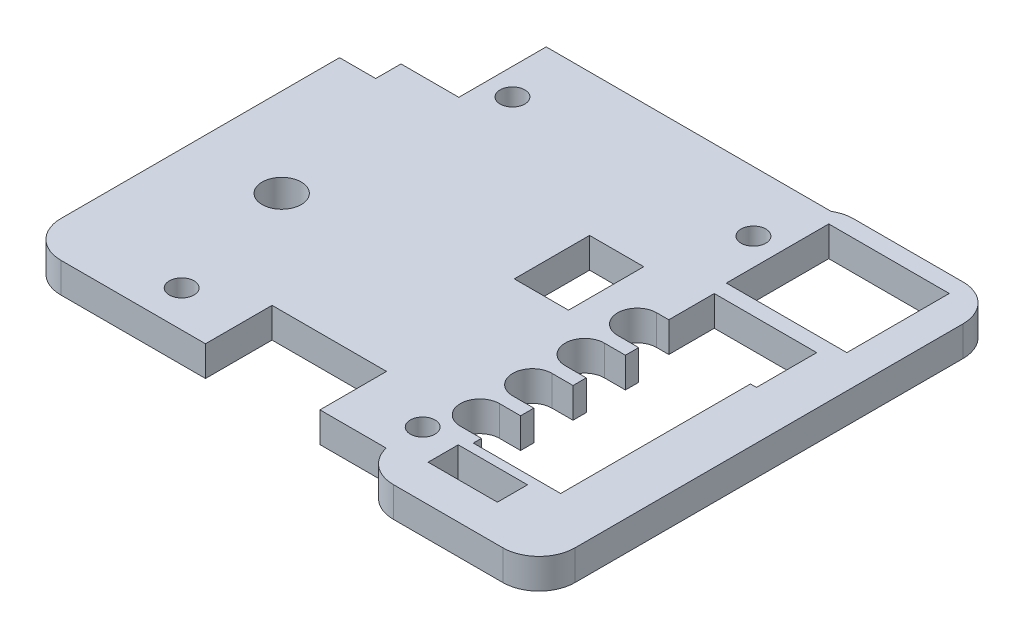
SolidWorks part; units mm, degrees
ref_plane "前视基准面" through (0, 0, 0) normal (0, 0, 1) x (1, 0, 0)
ref_plane "上视基准面" through (0, 0, 0) normal (0, 1, 0) x (1, 0, 0)
ref_plane "右视基准面" through (0, 0, 0) normal (1, 0, 0) x (0, 0, -1)
sketch "草图1" plane through (0, 0, 0) normal (0, 1, 0) x (1, 0, 0)
  line L0 (6, 0.3) -> (143.8, 0.3)
  line L1 (6, 0) -> (143.8, 0) construction
  line L2 (0, -6) -> (0, -68.8) construction
  line L3 (6, -74.8) -> (143.8, -74.8) construction
  line L4 (149.8, -6) -> (149.8, -68.8) construction
  line L5 (150.1, -6) -> (150.1, -68.8)
  line L6 (6, -75.1) -> (143.8, -75.1)
  line L7 (-0.3, -6) -> (-0.3, -68.8)
  arc A0 (143.8, 0) -> (149.8, -6) centre (143.8, -6) cw construction
  arc A1 (143.8, -74.8) -> (149.8, -68.8) centre (143.8, -68.8) ccw construction
  arc A2 (0, -68.8) -> (6, -74.8) centre (6, -68.8) ccw construction
  arc A3 (6, 0) -> (0, -6) centre (6, -6) ccw construction
  arc A4 (143.8, 0.3) -> (150.1, -6) centre (143.8, -6) cw
  arc A5 (143.8, -75.1) -> (150.1, -68.8) centre (143.8, -68.8) ccw
  arc A6 (-0.3, -68.8) -> (6, -75.1) centre (6, -68.8) ccw
  arc A7 (6, 0.3) -> (-0.3, -6) centre (6, -6) ccw
  point P7 (149.8, 0)
  point P12 (0, -74.8)
  point P15 (0, 0)
  dimension "D3" = 6
  dimension "D1" = 74.8
  dimension "D2" = 149.8
  dimension "D4" = 0.3
sketch "草图2" plane through (0, 0, 0) normal (0, -1, 0) x (-1, 0, 0)
  line L0 (-122.6, -55.35) -> (-108.9, -55.35) construction
  line L1 (-122.6, -69.85) -> (-108.9, -69.85) construction
  line L2 (-122.6, -69.85) -> (-122.6, -63.95) construction
  line L3 (-122.6, -63.95) -> (-108.9, -63.95) construction
  line L4 (-108.9, -69.85) -> (-108.9, -63.95) construction
  line L5 (-135.3, -1.25) -> (-35.3, -1.25) construction
  line L6 (-135.3, -1.25) -> (-135.3, -73.55) construction
  line L7 (-135.3, -73.55) -> (-35.3, -73.55) construction
  line L8 (-35.3, -1.25) -> (-35.3, -73.55) construction
  line L9 (-108.9, -61.25) -> (-108.9, -55.35) construction
  line L10 (-122.6, -61.25) -> (-108.9, -61.25) construction
  line L11 (-122.6, -61.25) -> (-122.6, -55.35) construction
  line L12 (-122.6, -46.75) -> (-108.9, -46.75) construction
  line L13 (-108.9, -52.65) -> (-108.9, -46.75) construction
  line L14 (-122.6, -52.65) -> (-108.9, -52.65) construction
  line L15 (-122.6, -52.65) -> (-122.6, -46.75) construction
  line L16 (-122.6, -38.15) -> (-108.9, -38.15) construction
  line L17 (-108.9, -44.05) -> (-108.9, -38.15) construction
  line L18 (-122.6, -44.05) -> (-108.9, -44.05) construction
  line L19 (-122.6, -44.05) -> (-122.6, -38.15) construction
  line L20 (0, -6) -> (0, -68.8) construction
  line L21 (-35.3, -73.55) -> (-0.8, -73.55) construction
  line L22 (-120.25, -26.65) -> (-111.25, -26.65) construction
  line L23 (-120.25, -26.65) -> (-120.25, -33.15) construction
  line L24 (-120.25, -33.15) -> (-111.25, -33.15) construction
  line L25 (-111.25, -26.65) -> (-111.25, -33.15) construction
  line L26 (-85.8, -48.75) -> (-81.1, -48.75) construction
  line L27 (-85.8, -48.75) -> (-85.8, -58.15) construction
  line L28 (-85.8, -58.15) -> (-81.1, -58.15) construction
  line L29 (-81.1, -48.75) -> (-81.1, -58.15) construction
  line L30 (-71.5, -48.65) -> (-68.2, -48.65) construction
  line L31 (-71.5, -48.65) -> (-71.5, -57.55) construction
  line L32 (-71.5, -57.55) -> (-68.2, -57.55) construction
  line L33 (-68.2, -48.65) -> (-68.2, -57.55) construction
  line L34 (-43.1, -45.05) -> (-38.6, -45.05) construction
  line L35 (-43.1, -45.05) -> (-43.1, -59.05) construction
  line L36 (-43.1, -59.05) -> (-38.6, -59.05) construction
  line L37 (-38.6, -45.05) -> (-38.6, -59.05) construction
  line L38 (-45.3, -61.55) -> (-40.8, -61.55) construction
  line L39 (-45.3, -61.55) -> (-45.3, -66.05) construction
  line L40 (-45.3, -66.05) -> (-40.8, -66.05) construction
  line L41 (-40.8, -61.55) -> (-40.8, -66.05) construction
  line L42 (-0.8, -73.55) -> (-0.8, -1.25) construction
  line L43 (-0.8, -1.25) -> (-35.3, -1.25) construction
  line L44 (-149.8, -6) -> (-149.8, -68.8) construction
  line L45 (-30.8, -34.65) -> (-27.3, -34.65) construction
  line L46 (-30.8, -34.65) -> (-30.8, -40.15) construction
  line L47 (-30.8, -40.15) -> (-27.3, -40.15) construction
  line L48 (-27.3, -34.65) -> (-27.3, -40.15) construction
  line L49 (-120.75, -33.65) -> (-110.75, -33.65)
  line L50 (-110.75, -26.15) -> (-110.75, -33.65)
  line L51 (-120.75, -26.15) -> (-110.75, -26.15)
  line L52 (-120.75, -26.15) -> (-120.75, -33.65)
  line L53 (-86.3, -48.25) -> (-86.3, -58.65)
  line L54 (-86.3, -58.65) -> (-80.6, -58.65)
  line L55 (-80.6, -48.25) -> (-80.6, -58.65)
  line L56 (-86.3, -48.25) -> (-80.6, -48.25)
  line L57 (-72, -48.15) -> (-72, -58.05)
  line L58 (-72, -58.05) -> (-67.7, -58.05)
  line L59 (-67.7, -48.15) -> (-67.7, -58.05)
  line L60 (-72, -48.15) -> (-67.7, -48.15)
  line L61 (-31.3, -34.15) -> (-31.3, -40.65)
  line L62 (-31.3, -40.65) -> (-26.8, -40.65)
  line L63 (-26.8, -34.15) -> (-26.8, -40.65)
  line L64 (-31.3, -34.15) -> (-26.8, -34.15)
  line L65 (-43.6, -44.55) -> (-43.6, -59.55)
  line L66 (-43.6, -59.55) -> (-38.1, -59.55)
  line L67 (-38.1, -44.55) -> (-38.1, -59.55)
  line L68 (-43.6, -44.55) -> (-38.1, -44.55)
  line L69 (-45.8, -61.05) -> (-45.8, -66.55)
  line L70 (-45.8, -66.55) -> (-40.3, -66.55)
  line L71 (-40.3, -61.05) -> (-40.3, -66.55)
  line L72 (-45.8, -61.05) -> (-40.3, -61.05)
  line L73 (-122.9, -44.35) -> (-108.6, -44.35)
  line L74 (-108.6, -44.35) -> (-108.6, -37.85)
  line L75 (-122.9, -37.85) -> (-108.6, -37.85)
  line L76 (-122.9, -44.35) -> (-122.9, -37.85)
  line L77 (-122.9, -52.95) -> (-108.6, -52.95)
  line L78 (-108.6, -52.95) -> (-108.6, -46.45)
  line L79 (-122.9, -46.45) -> (-108.6, -46.45)
  line L80 (-122.9, -52.95) -> (-122.9, -46.45)
  line L81 (-122.9, -61.55) -> (-108.6, -61.55)
  line L82 (-108.6, -61.55) -> (-108.6, -55.05)
  line L83 (-122.9, -55.05) -> (-108.6, -55.05)
  line L84 (-122.9, -61.55) -> (-122.9, -55.05)
  line L85 (-122.9, -70.15) -> (-108.6, -70.15)
  line L86 (-108.6, -70.15) -> (-108.6, -63.65)
  line L87 (-122.9, -63.65) -> (-108.6, -63.65)
  line L88 (-122.9, -70.15) -> (-122.9, -63.65)
  circle A0 centre (-103.2, -9.35) radius 1.65 construction
  circle A1 centre (-103.2, -64.25) radius 1.65 construction
  circle A2 centre (-63.2, -64.25) radius 1.65 construction
  circle A3 centre (-63.2, -9.35) radius 1.65 construction
  circle A4 centre (-130.8, -5.6) radius 1.25 construction
  circle A5 centre (-131.1, -55.65) radius 1.25 construction
  circle A6 centre (-47.7, -4.85) radius 1.25 construction
  circle A7 centre (-48.1, -68.75) radius 1.25 construction
  circle A8 centre (-22.8, -70.3) radius 1.25 construction
  circle A9 centre (-5.05, -71.05) radius 1.25 construction
  circle A10 centre (-5.05, -3.25) radius 1.25 construction
  circle A11 centre (-19, -37.4) radius 3.6 construction
  circle A12 centre (-103.2, -9.35) radius 2.05
  circle A13 centre (-63.2, -9.35) radius 2.05
  circle A14 centre (-63.2, -64.25) radius 2.05
  circle A15 centre (-103.2, -64.25) radius 2.05
  circle A16 centre (-19, -37.4) radius 4.1
  circle A17 centre (-130.8, -5.6) radius 1.75
  circle A18 centre (-131.1, -55.65) radius 1.75
  circle A19 centre (-48.1, -68.75) radius 1.75
  circle A20 centre (-22.8, -70.3) radius 1.75
  circle A21 centre (-5.05, -71.05) radius 1.75
  circle A22 centre (-5.05, -3.25) radius 1.75
  circle A23 centre (-47.7, -4.85) radius 1.75
  point P22 (0, -37.4)
  point P23 (-135.3, -37.4)
  point P28 (-115.75, -33.15)
  point P29 (-115.75, -38.15)
  point P30 (-111.25, -29.9)
  point P31 (-108.9, -41.1)
  point P79 (-0.8, -37.4)
  point P81 (-27.3, -37.4)
  dimension "D21" = 3.3
  dimension "D34" = 2.5
  dimension "D53" = 7.2
  dimension "D1" = 13.7
  dimension "D2" = 5.9
  dimension "D3" = 72.3
  dimension "D4" = 3.7
  dimension "D5" = 12.7
  dimension "D7" = 14.5
  dimension "D8" = 100
  dimension "D9" = 2.7
  dimension "D10" = 9
  dimension "D11" = 6.5
  dimension "D12" = 11.2
  dimension "D13" = 15.4
  dimension "D14" = 9.4
  dimension "D15" = 4.7
  dimension "D16" = 23.1
  dimension "D17" = 3.3
  dimension "D18" = 8.9
  dimension "D19" = 16
  dimension "D20" = 37.4
  dimension "D22" = 8.1
  dimension "D23" = 32.1
  dimension "D24" = 40
  dimension "D25" = 9.3
  dimension "D26" = 14
  dimension "D27" = 4.5
  dimension "D28" = 4.5
  dimension "D29" = 4.5
  dimension "D30" = 3.3
  dimension "D31" = 5.5
  dimension "D32" = 7.5
  dimension "D33" = 14.5
  dimension "D35" = 34.5
  dimension "D36" = 2
  dimension "D37" = 4.25
  dimension "D38" = 2.5
  dimension "D39" = 3.25
  dimension "D40" = 22
  dimension "D41" = 4.8
  dimension "D42" = 12.8
  dimension "D43" = 3.6
  dimension "D44" = 12.4
  dimension "D45" = 4.35
  dimension "D46" = 4.5
  dimension "D47" = 4.2
  dimension "D48" = 17.9
  dimension "D49" = 18.2
  dimension "D50" = 3.5
  dimension "D51" = 5.5
  dimension "D52" = 8.3
  dimension "D54" = 0.4
  dimension "D55" = 0.5
  dimension "D56" = 0.5
  dimension "D57" = 0.5
  dimension "D58" = 0.3
  dimension "D6" = 4
sketch "草图3" plane through (0, 0, 0) normal (0, 1, 0) x (1, 0, 0)
  line L0 (135.3, -1.25) -> (135.3, -73.55) construction
  line L1 (143.8, 0) -> (135.3, 0)
  line L2 (149.8, -6) -> (149.8, -68.8)
  line L3 (143.8, -74.8) -> (135.3, -74.8)
  line L4 (135.3, 0) -> (135.3, -74.8)
  line L5 (6, -74.8) -> (143.8, -74.8) construction
  arc A0 (143.8, 0) -> (149.8, -6) centre (143.8, -6) cw
  arc A1 (149.8, -68.8) -> (143.8, -74.8) centre (143.8, -68.8) cw
  point P17 (149.8, 0)
  dimension "D1" = 6
sketch "草图4" plane through (0, 0, 0) normal (0, 1, 0) x (1, 0, 0)
  line L0 (122.9, -62.85) -> (108.6, -62.85)
  line L1 (122.6, -63.15) -> (108.9, -63.15) construction
  line L2 (122.6, -63.15) -> (122.6, -70.65) construction
  line L3 (122.6, -70.65) -> (108.9, -70.65) construction
  line L4 (108.9, -63.15) -> (108.9, -70.65) construction
  line L5 (122.6, -69.85) -> (122.6, -63.95) construction
  line L6 (108.6, -62.85) -> (108.6, -70.95)
  line L7 (108.9, -69.85) -> (108.9, -63.95) construction
  line L8 (122.6, -54.55) -> (108.9, -54.55) construction
  line L9 (108.9, -54.55) -> (108.9, -62.05) construction
  line L10 (122.6, -62.05) -> (108.9, -62.05) construction
  line L11 (122.6, -54.55) -> (122.6, -62.05) construction
  line L12 (122.6, -45.95) -> (108.9, -45.95) construction
  line L13 (108.9, -45.95) -> (108.9, -53.45) construction
  line L14 (122.6, -53.45) -> (108.9, -53.45) construction
  line L15 (122.6, -45.95) -> (122.6, -53.45) construction
  line L16 (122.6, -37.35) -> (108.9, -37.35) construction
  line L17 (108.9, -37.35) -> (108.9, -44.85) construction
  line L18 (122.6, -44.85) -> (108.9, -44.85) construction
  line L19 (122.6, -37.35) -> (122.6, -44.85) construction
  line L20 (122.9, -70.95) -> (108.6, -70.95)
  line L21 (122.9, -62.85) -> (122.9, -70.95)
  line L22 (122.9, -54.25) -> (108.6, -54.25)
  line L23 (108.6, -54.25) -> (108.6, -62.35)
  line L24 (122.9, -62.35) -> (108.6, -62.35)
  line L25 (122.9, -54.25) -> (122.9, -62.35)
  line L26 (122.9, -45.65) -> (108.6, -45.65)
  line L27 (108.6, -45.65) -> (108.6, -53.75)
  line L28 (122.9, -53.75) -> (108.6, -53.75)
  line L29 (122.9, -45.65) -> (122.9, -53.75)
  line L30 (122.9, -37.05) -> (108.6, -37.05)
  line L31 (108.6, -37.05) -> (108.6, -45.15)
  line L32 (122.9, -45.15) -> (108.6, -45.15)
  line L33 (122.9, -37.05) -> (122.9, -45.15)
  point P11 (108.9, -66.9)
  point P12 (108.9, -66.9)
  dimension "D1" = 7.5
  dimension "D3" = 1.1
  dimension "D4" = 0.3
  dimension "D2" = 4
extrude "拉伸-薄壁1" add sketch "草图2" along normal blind 5 thin contours A13 | A12 | A14 | A15
sketch "草图6" plane through (0, 0, 0) normal (0, 1, 0) x (1, 0, 0)
  line L0 (127.2, 1.45) -> (109.0462, 1.45)
  line L1 (133.2, -4.55) -> (133.2, -68.95)
  line L2 (127.2, -74.95) -> (109.0462, -74.95)
  line L3 (33.4345, -36.75) -> (43.3021, -36.75) construction
  line L4 (63.2, 0.65) -> (106.0528, 0.65)
  line L6 (63.2, 0.65) -> (45.7, 0.65)
  line L10 (122.9, -70.95) -> (108.6, -70.95) construction
  line L11 (108.6, -62.85) -> (108.6, -70.95) construction
  line L12 (43.2, -1.85) -> (43.2, -64.3)
  line L13 (103.2, -70.3) -> (49.2, -70.3)
  circle A1 centre (103.2, -64.25) radius 6.05 construction
  arc A3 (133.2, -4.55) -> (127.2, 1.45) centre (127.2, -4.55) ccw
  arc A4 (109.0462, -74.95) -> (103.2, -70.3) centre (109.0462, -68.95) cw
  circle A5 centre (63.2, -64.25) radius 6.05 construction
  arc A6 (133.2, -68.95) -> (127.2, -74.95) centre (127.2, -68.95) cw
  arc A7 (109.0462, 1.45) -> (106.0528, 0.65) centre (109.0462, -4.55) ccw
  arc A9 (43.2, -64.3) -> (49.2, -70.3) centre (49.2, -64.3) ccw
  circle A10 centre (103.2, -9.35) radius 2.05 construction
  circle A11 centre (103.2, -64.25) radius 2.05 construction
  circle A12 centre (63.2, -64.25) radius 2.05 construction
  circle A13 centre (103.2, -9.35) radius 2.05
  circle A14 centre (103.2, -64.25) radius 2.05
  circle A15 centre (63.2, -64.25) radius 2.05
  circle A16 centre (63.2, -9.35) radius 2.05 construction
  circle A17 centre (63.2, -9.35) radius 2.05
  arc A18 (45.7, 0.65) -> (43.2, -1.85) centre (45.7, -1.85) ccw
  point P37 (105.6, -74.95)
  point P42 (130.9, -6.15)
  dimension "D6" = 6
  dimension "D7" = 5
  dimension "D8" = 6
  dimension "D9" = 6
  dimension "D10" = 6
  dimension "D11" = 6
  dimension "D2" = 27.5
  dimension "D3" = 4
  dimension "D4" = 3
  dimension "D5" = 20
  dimension "D12" = 30
  dimension "D13" = 10
extrude "凸台-拉伸1" add sketch "草图6" against normal up to surface (5 mm away) up to face at (97.15, -5, 9.35)
sketch "草图7" plane through (0, -5, 3) normal (0, -1, 0) x (1, 0, 0)
  line L9 (80.466, 15.85) -> (96.6871, 15.85) construction
  line L43 (107.2, -14.628) -> (107.2, -27.7853) construction
  line L44 (108.9, 22) -> (108.9, 67) construction
  line L45 (122.6, 67) -> (108.9, 67) construction
  line L46 (122.6, 22) -> (122.6, 67) construction
  line L47 (122.6, 22) -> (108.9, 22) construction
  line L48 (120.2, 9.55) -> (113.2, 9.55)
  line L49 (120.2, 4.55) -> (120.2, 9.55)
  line L50 (113.2, 4.55) -> (120.2, 4.55)
  line L51 (113.2, 9.55) -> (113.2, 4.55)
  line L52 (80.4, 48.65) -> (80.4, 33.65)
  line L53 (85.4, 48.65) -> (80.4, 48.65)
  line L54 (97.9, 36.55) -> (89.9, 36.55)
  line L55 (97.9, 25.55) -> (97.9, 36.55)
  line L56 (89.9, 25.55) -> (97.9, 25.55)
  line L57 (89.9, 36.55) -> (89.9, 25.55)
  line L58 (66.4, 33.65) -> (80.4, 33.65)
  line L59 (50.4, 54.65) -> (50.4, 33.65)
  line L60 (85.4, 54.65) -> (50.4, 54.65)
  line L61 (85.4, 48.65) -> (85.4, 54.65)
  line L62 (47.4, 10.15) -> (66.4, 10.15)
  line L63 (47.4, 33.65) -> (47.4, 10.15)
  line L64 (50.4, 33.65) -> (47.4, 33.65)
  line L65 (66.4, 10.15) -> (66.4, 15.35)
  line L66 (66.4, 24.35) -> (72.4, 24.35)
  line L67 (66.4, 24.35) -> (66.4, 33.65)
  line L68 (72.4, 15.35) -> (66.4, 15.35)
  line L69 (122.9, 21.7) -> (122.9, 67.3)
  line L70 (122.9, 67.3) -> (108.6, 67.3)
  line L71 (72.4, 24.35) -> (72.4, 15.35)
  line L72 (92.2, 15.35) -> (75.2, 15.35)
  line L73 (92.2, 23.55) -> (92.2, 15.35)
  line L74 (75.2, 23.55) -> (92.2, 23.55)
  line L75 (107.7, 23.55) -> (107.7, 15.35)
  line L76 (98.2, 23.55) -> (107.7, 23.55)
  line L77 (98.2, 15.35) -> (98.2, 23.55)
  line L78 (107.7, 15.35) -> (98.2, 15.35)
  line L79 (75.2, 15.35) -> (75.2, 23.55)
  line L80 (108.6, 21.7) -> (108.6, 67.3)
  line L81 (122.9, 21.7) -> (108.6, 21.7)
  circle A0 centre (103.2, 61.25) radius 2.05 construction
  circle A1 centre (103.2, 61.25) radius 2.05
  circle A5 centre (59.2, 61.25) radius 2.05
  circle A6 centre (103.2, 61.25) radius 2.05
extrude "切除-拉伸1" [suppressed] cut sketch "草图7" against normal blind 5 contours L81 L69 L70 L80 | L78 L75 L76 L77 | L54 L57 L56 L55 | L79 L72 L73 L74 | L71 L66 L67 L58 L52 L53 L61 L60 L59 L64 L63 L62 L65 L68
sketch "草图8" plane through (0, 0, 0) normal (0, -1, 0) x (1, 0, 0)
  line L3 (106.2, 28.95) -> (106.2, 55.65) construction
  line L6 (133.2, 68.95) -> (133.2, 4.55) construction
  line L7 (109.0462, 74.95) -> (127.2, 74.95) construction
  line L9 (80.466, -18.85) -> (96.6871, -18.85) construction
  line L10 (107.2, 11.628) -> (107.2, 24.7853) construction
  line L14 (5.1637, 36.85) -> (19.0276, 36.85) construction
  line L15 (106.2, 60.7) -> (109.7, 60.7)
  line L18 (63.2, 64.25) -> (46.0308, 64.25) construction
  line L19 (67.2, 40.45) -> (49.2, 40.45)
  line L20 (106.2, 54.2) -> (109.7, 54.2)
  line L22 (67.2, 13.45) -> (67.2, 40.45)
  line L23 (49.2, 13.45) -> (67.2, 13.45)
  line L24 (49.2, 40.45) -> (49.2, 13.45)
  line L25 (98.5, 35.95) -> (89.5, 35.95)
  line L26 (98.5, 23.45) -> (98.5, 35.95)
  line L27 (89.5, 23.45) -> (98.5, 23.45)
  line L28 (89.5, 35.95) -> (89.5, 23.45)
  line L29 (108.2, 30.95) -> (125.2, 30.95) construction
  line L30 (128.2, 18.45) -> (108.2, 18.45)
  line L31 (128.2, 2.45) -> (128.2, 18.45)
  line L32 (108.2, 2.45) -> (128.2, 2.45)
  line L37 (108.2, 18.45) -> (108.2, 2.45)
  line L38 (125.2, 20.95) -> (125.2, 30.95)
  line L47 (125.2, 30.95) -> (124.2, 30.95)
  line L48 (108.2, 30.95) -> (108.2, 20.95)
  line L49 (108.2, 30.95) -> (109.7, 30.95)
  line L50 (125.2, 20.95) -> (108.2, 20.95)
  line L51 (111.7, 64.75) -> (122.2, 64.75)
  line L52 (122.2, 62.75) -> (122.2, 69.95)
  line L53 (124.2, 30.95) -> (124.2, 63.75)
  line L54 (109.7, 63.75) -> (124.2, 63.75)
  line L55 (111.7, 69.95) -> (122.2, 69.95)
  line L56 (111.7, 69.95) -> (111.7, 62.75)
  line L57 (109.7, 30.95) -> (109.7, 63.75)
  line L58 (75.2, 64.35) -> (89.2, 64.35)
  line L59 (75.2, 73.35) -> (75.2, 64.35)
  line L60 (89.2, 73.35) -> (75.2, 73.35)
  line L61 (89.2, 64.35) -> (89.2, 73.35)
  line L62 (106.2, 51.8) -> (109.7, 51.8)
  line L63 (106.2, 45.3) -> (109.7, 45.3)
  line L64 (106.2, 42.9) -> (109.7, 42.9)
  line L65 (106.2, 36.4) -> (109.7, 36.4)
  line L66 (106.2, 34) -> (109.7, 34)
  line L67 (106.2, 27.5) -> (108.2, 27.5)
  line L68 (109.7, 34) -> (109.7, 27.5)
  line L69 (109.7, 27.5) -> (108.2, 27.5)
  line L70 (109.7, 36.4) -> (109.7, 42.9)
  line L71 (109.7, 45.3) -> (109.7, 51.8)
  line L72 (109.7, 54.2) -> (109.7, 60.7)
  circle A1 centre (57.9, 42.45) radius 3.25
  circle A2 centre (103.2, 9.35) radius 2.4
  circle A3 centre (106.2, 57.45) radius 3.25
  circle A4 centre (63.2, 9.35) radius 2.4
  circle A5 centre (103.2, 64.25) radius 2.4 construction
  circle A10 centre (106.2, 48.55) radius 3.25
  circle A11 centre (63.2, 64.25) radius 2.4 construction
  circle A14 centre (106.2, 39.65) radius 3.25
  circle A15 centre (106.2, 30.75) radius 3.25
  dimension "D7" = 27.5
  dimension "D1" = 10
  dimension "D3" = 8.9
  dimension "D2" = 27
  dimension "D4" = 8.9
  dimension "D5" = 8.9
  dimension "D6" = 17.5
  dimension "D8" = 20
extrude "切除-拉伸2" [suppressed] cut sketch "草图8" along normal through all
sketch "草图10" plane through (0, 0, 0) normal (0, -1, 0) x (1, 0, 0)
  line L0 (67.2, 40.45) -> (49.2, 40.45)
  line L1 (49.2, 40.45) -> (49.2, 13.45)
  line L2 (49.2, 13.45) -> (67.2, 13.45)
  line L3 (67.2, 13.45) -> (67.2, 40.45)
sketch "草图9" plane through (0, -5, 0) normal (0, -1, 0) x (1, 0, 0)
  line L0 (58.8, 13.85) -> (58.8, 1.85)
  line L2 (58.8, 1.85) -> (45.8, 1.85)
  line L3 (45.8, 1.85) -> (45.8, 13.85)
  line L4 (45.8, 13.85) -> (58.8, 13.85)
  circle A0 centre (63.2, 9.35) radius 2.05 construction
  circle A1 centre (63.2, 9.35) radius 2.05 construction
  dimension "D1" = 13
  dimension "D2" = 4.5
  dimension "D3" = 4.4
  dimension "D4" = 12
extrude "切除-拉伸3" [suppressed] cut sketch "草图9" against normal through all
extrude "切除-拉伸5_电源模块(一般不用，焊接模块时才需要)" [suppressed] cut sketch "草图10" along normal blind 2
sketch "草图11" plane through (0, -5, 5) normal (0, -1, 0) x (1, 0, 0)
  line L9 (80.466, -18.85) -> (96.6871, -18.85) construction
  line L10 (107.2, 11.628) -> (107.2, 24.7853) construction
  line L19 (106.2, -55.55) -> (106.2, -28.85) construction
  line L54 (63.2, 4.35) -> (46.0308, 4.35) construction
  line L55 (108.2, 25.85) -> (125.2, 25.85) construction
  line L56 (45.8, 13.05) -> (49.2, 13.05)
  line L57 (45.8, 13.05) -> (45.8, 6.35)
  line L58 (39.8, 13.05) -> (45.8, 13.05)
  line L59 (39.8, 6.35) -> (39.8, 13.05)
  line L60 (45.8, 6.35) -> (39.8, 6.35)
  line L61 (45.8, -3.15) -> (58.8, -3.15)
  line L62 (45.8, 8.85) -> (45.8, -3.15)
  line L63 (73.2, 54.25) -> (92.2, 54.25)
  line L64 (73.2, 66.25) -> (73.2, 54.25)
  line L65 (92.2, 66.25) -> (73.2, 66.25)
  line L66 (92.2, 54.25) -> (92.2, 66.25)
  line L67 (127.7, 13.35) -> (107.7, 13.35)
  line L68 (127.7, -3.65) -> (127.7, 13.35)
  line L69 (107.7, -3.65) -> (127.7, -3.65)
  line L70 (107.7, 13.35) -> (107.7, -3.65)
  line L71 (58.8, 8.85) -> (45.8, 8.85)
  line L72 (58.8, -3.15) -> (58.8, 8.85)
  line L73 (98.5, 30.35) -> (89.5, 30.35)
  line L74 (98.5, 17.85) -> (98.5, 30.35)
  line L75 (89.5, 17.85) -> (98.5, 17.85)
  line L76 (89.5, 30.35) -> (89.5, 17.85)
  line L77 (61.15, 37.35) -> (61.15, 35.35)
  line L78 (54.65, 37.35) -> (54.65, 35.35)
  line L79 (106.2, 56) -> (109.7, 56)
  line L80 (106.2, 49.5) -> (109.7, 49.5)
  line L81 (106.2, 47.3) -> (109.7, 47.3)
  line L82 (106.2, 40.8) -> (109.7, 40.8)
  line L83 (109.7, 38.6) -> (106.2, 38.6)
  line L84 (109.7, 32.1) -> (109.7, 38.6)
  line L85 (106.2, 32.1) -> (109.7, 32.1)
  line L86 (106.2, 29.9) -> (109.7, 29.9)
  line L87 (106.2, 23.4) -> (108.2, 23.4)
  line L88 (125.2, 15.85) -> (125.2, 25.85)
  line L89 (108.7, 58.85) -> (120.2, 58.85)
  line L90 (67.2, 35.35) -> (49.2, 35.35)
  line L91 (67.2, 8.35) -> (67.2, 35.35)
  line L92 (120.2, 57.35) -> (120.2, 63.85)
  line L93 (124.2, 57.35) -> (120.2, 57.35)
  line L94 (124.2, 25.85) -> (124.2, 57.35)
  line L95 (125.2, 25.85) -> (124.2, 25.85)
  line L96 (49.2, 8.35) -> (67.2, 8.35)
  line L97 (109.7, 57.35) -> (124.2, 57.35)
  line L98 (108.7, 63.85) -> (120.2, 63.85)
  line L99 (108.2, 25.85) -> (108.2, 15.85)
  line L100 (49.2, 35.35) -> (49.2, 8.35)
  line L101 (108.7, 63.85) -> (108.7, 57.35)
  line L102 (109.7, 25.85) -> (109.7, 57.35)
  line L103 (108.2, 25.85) -> (109.7, 25.85)
  line L104 (125.2, 15.85) -> (108.2, 15.85)
  circle A13 centre (63.2, 4.35) radius 2.4 construction
  circle A14 centre (103.2, 4.35) radius 2.4 construction
  circle A15 centre (57.9, 37.35) radius 3.25
  circle A16 centre (106.2, 52.75) radius 3.25
  circle A17 centre (106.2, 44.05) radius 3.25
  circle A18 centre (106.2, 35.35) radius 3.25
  circle A19 centre (106.2, 26.65) radius 3.25
  circle A20 centre (63.2, 59.25) radius 2.4
  circle A21 centre (103.2, 59.25) radius 2.4
extrude "切除-拉伸4" cut sketch "草图11" against normal through all contours L98 L101 L89 L92 | L79 A16 L80 L102 | L81 A17 L82 L102 | L83 A18 L85 L84 | L86 A19 L103 L102 | L99 A19 L87 | L100 L56 L57 L71 | L63 L66 L65 L64 | L74 L73 L76 L75 | L67 L70 L69 L68 | A15
sketch "草图12" plane through (0, -5, 0) normal (0, -1, 0) x (1, 0, 0)
  line L0 (58.8, 1.85) -> (58.8, -0.65)
  line L1 (106.0528, -0.65) -> (45.7, -0.65) construction
  line L2 (43.2, 1.85) -> (43.2, 11.35) construction
  line L3 (45.8, 11.35) -> (43.2, 11.35) construction
  line L4 (45.8, 11.35) -> (45.8, 1.85) construction
  line L5 (45.8, 1.85) -> (58.8, 1.85) construction
  line L6 (106.0528, -0.65) -> (45.7, -0.65)
  line L7 (43.2, 1.85) -> (43.2, 11.35)
  line L8 (45.8, 11.35) -> (43.2, 11.35)
  line L9 (45.8, 11.35) -> (45.8, 1.85)
  line L10 (45.8, 1.85) -> (58.8, 1.85)
  arc A0 (43.2, 1.85) -> (45.7, -0.65) centre (45.7, 1.85) ccw construction
  arc A1 (43.2, 1.85) -> (45.7, -0.65) centre (45.7, 1.85) ccw
extrude "切除-拉伸5" cut sketch "草图12" against normal through all contours L7 A1 L6 L0 L10 L9 L8
equation "\"D1@草图3\"=\"D3@草图1\""
